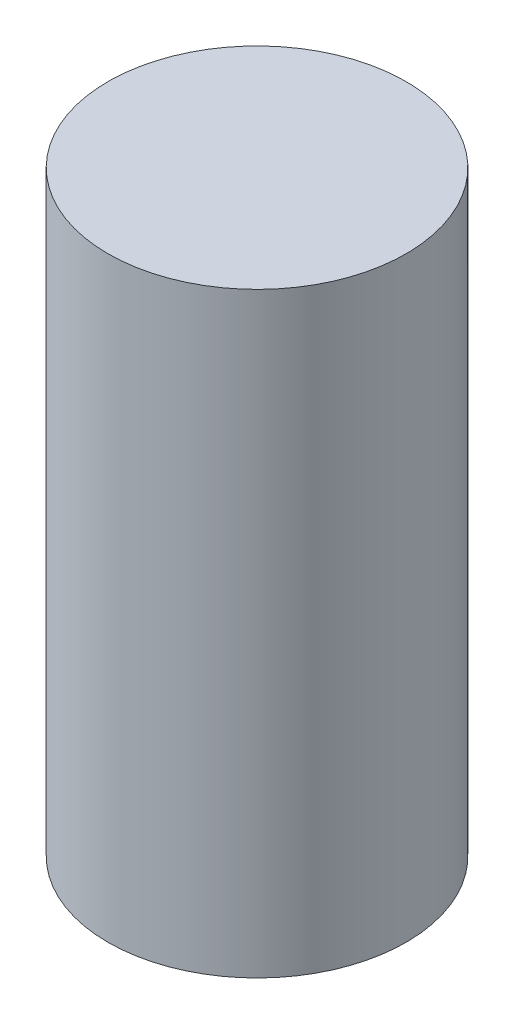
SolidWorks part; units mm, degrees
material "AISI 1020"
ref_plane "Alzado" through (0, 0, 0) normal (0, 0, 1) x (1, 0, 0)
ref_plane "Planta" through (0, 0, 0) normal (0, 1, 0) x (1, 0, 0)
ref_plane "Vista lateral" through (0, 0, 0) normal (1, 0, 0) x (0, 0, -1)
sketch "Croquis1" plane through (0, 0, 0) normal (0, 1, 0) x (1, 0, 0)
  circle A0 centre (0, 0) radius 25
  dimension "D1" = 50
extrude "Saliente-Extruir1" add sketch "Croquis1" along normal blind 100
